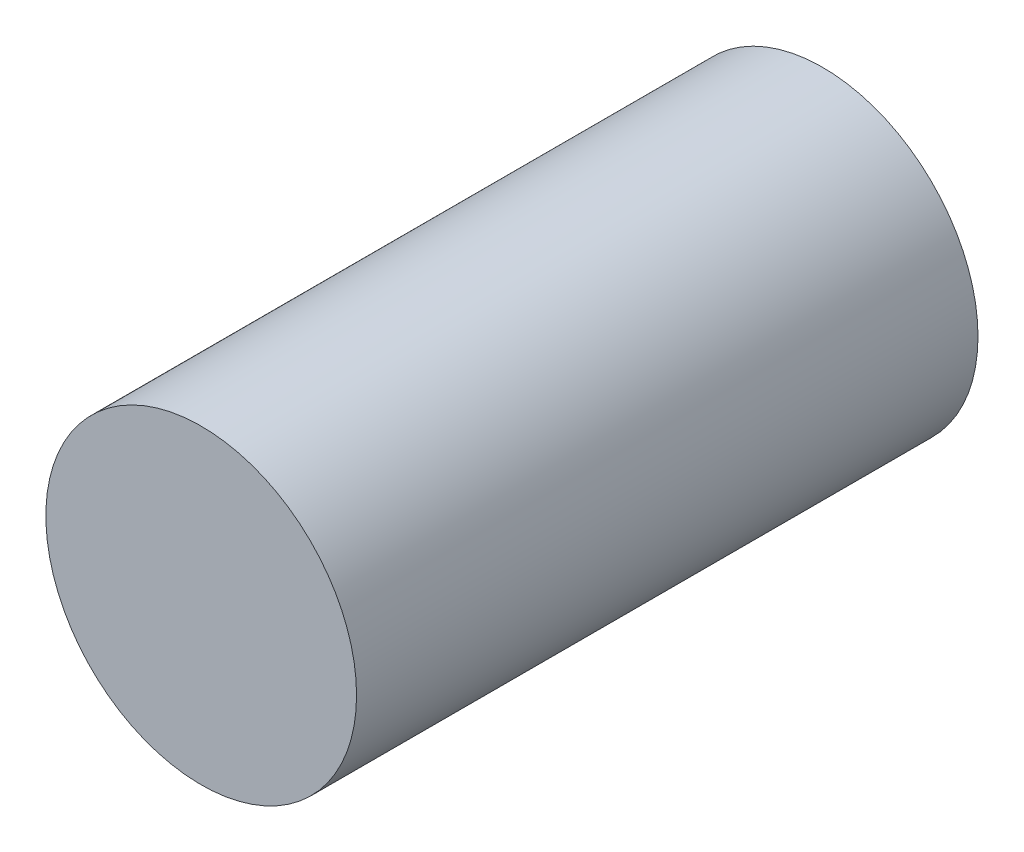
SolidWorks part; units mm, degrees
ref_plane "Front Plane" through (0, 0, 0) normal (0, 0, 1) x (1, 0, 0)
ref_plane "Top Plane" through (0, 0, 0) normal (0, 1, 0) x (1, 0, 0)
ref_plane "Right Plane" through (0, 0, 0) normal (1, 0, 0) x (0, 0, -1)
sketch "Sketch1" plane through (0, 0, 0) normal (0, 0, 1) x (1, 0, 0)
  circle A0 centre (0, 0) radius 12.5
extrude "Boss-Extrude1" add sketch "Sketch1" against normal blind 50
